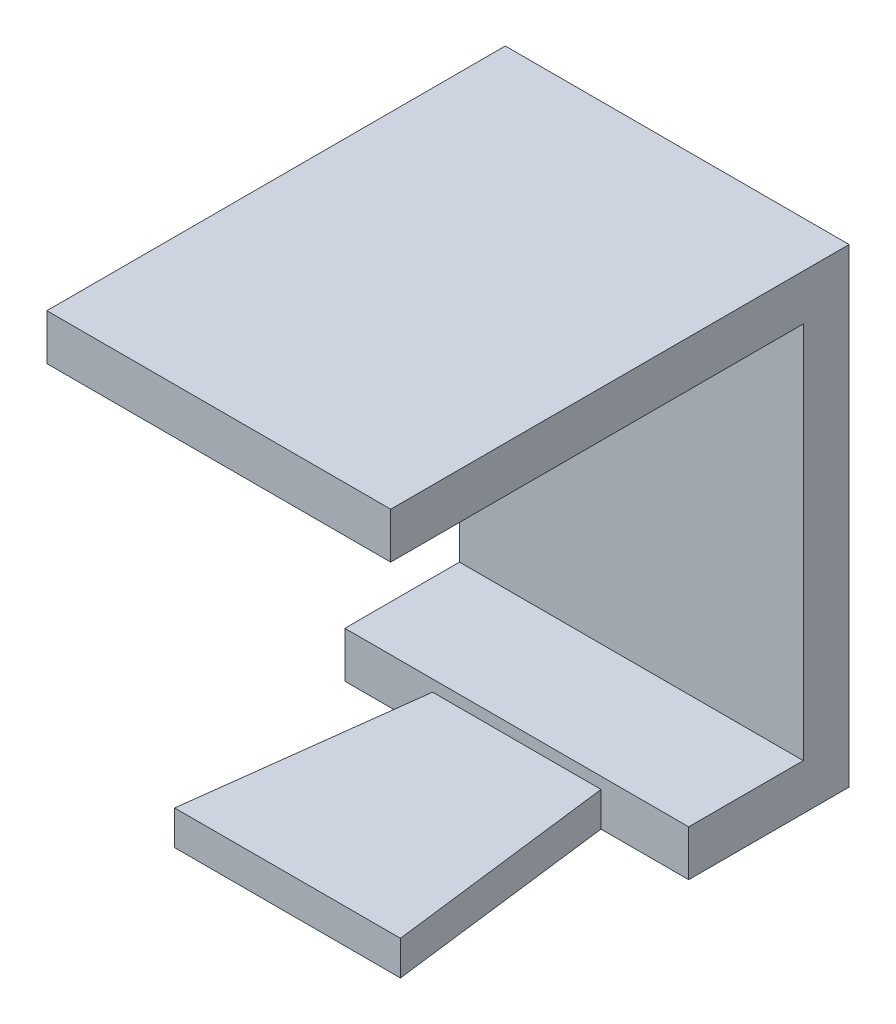
SolidWorks part; units mm, degrees
ref_plane "Front Plane" through (0, 0, 0) normal (0, 0, 1) x (1, 0, 0)
ref_plane "Top Plane" through (0, 0, 0) normal (0, 1, 0) x (1, 0, 0)
ref_plane "Right Plane" through (0, 0, 0) normal (1, 0, 0) x (0, 0, -1)
sketch "Sketch1" plane through (0, 0, 0) normal (0, 0, 1) x (1, 0, 0)
  line L1 (0, 0) -> (30, 0)
  line L2 (0, 0) -> (0, 33)
  line L3 (0, 33) -> (30, 33)
  line L4 (30, 0) -> (30, 33)
  dimension "D1" = 30
  dimension "D2" = 33
extrude "Boss-Extrude1" add sketch "Sketch1" along normal blind 4
sketch "Sketch2" plane through (0, 33, 0) normal (0, 1, 0) x (1, 0, 0)
  line L0 (30, -4) -> (30, 0) construction
  line L1 (0, 0) -> (30, 0)
  line L2 (0, 0) -> (0, -40)
  line L3 (0, -40) -> (30, -40)
  line L4 (30, 0) -> (30, -40)
  dimension "D1" = 40
extrude "Boss-Extrude2" add sketch "Sketch2" along normal blind 4
sketch "Sketch4" plane through (0, 0, 0) normal (0, -1, 0) x (1, 0, 0)
  line L0 (30, 40) -> (30, 4) construction
  line L1 (0, 0) -> (30, 0)
  line L2 (0, 0) -> (0, 14)
  line L3 (0, 14) -> (30, 14)
  line L4 (30, 0) -> (30, 14)
  dimension "D1" = 14
extrude "Boss-Extrude3" add sketch "Sketch4" along normal blind 4
sketch "Sketch3" plane through (0, -4, 0) normal (0, -1, 0) x (1, 0, 0)
  line L0 (7.65, 14) -> (22.35, 14)
  line L2 (22.35, 14) -> (24.85, 34)
  line L3 (24.85, 34) -> (5.15, 34)
  line L4 (5.15, 34) -> (7.65, 14)
  line L5 (30, 14) -> (0, 14) construction
  line L6 (0, 4) -> (0, 40) construction
  dimension "D1" = 19.7
  dimension "D2" = 14.7
  dimension "D3" = 20
  dimension "D4" = 5.15
  dimension "D5" = 7.65
extrude "Boss-Extrude4" add sketch "Sketch3" against normal blind 3
